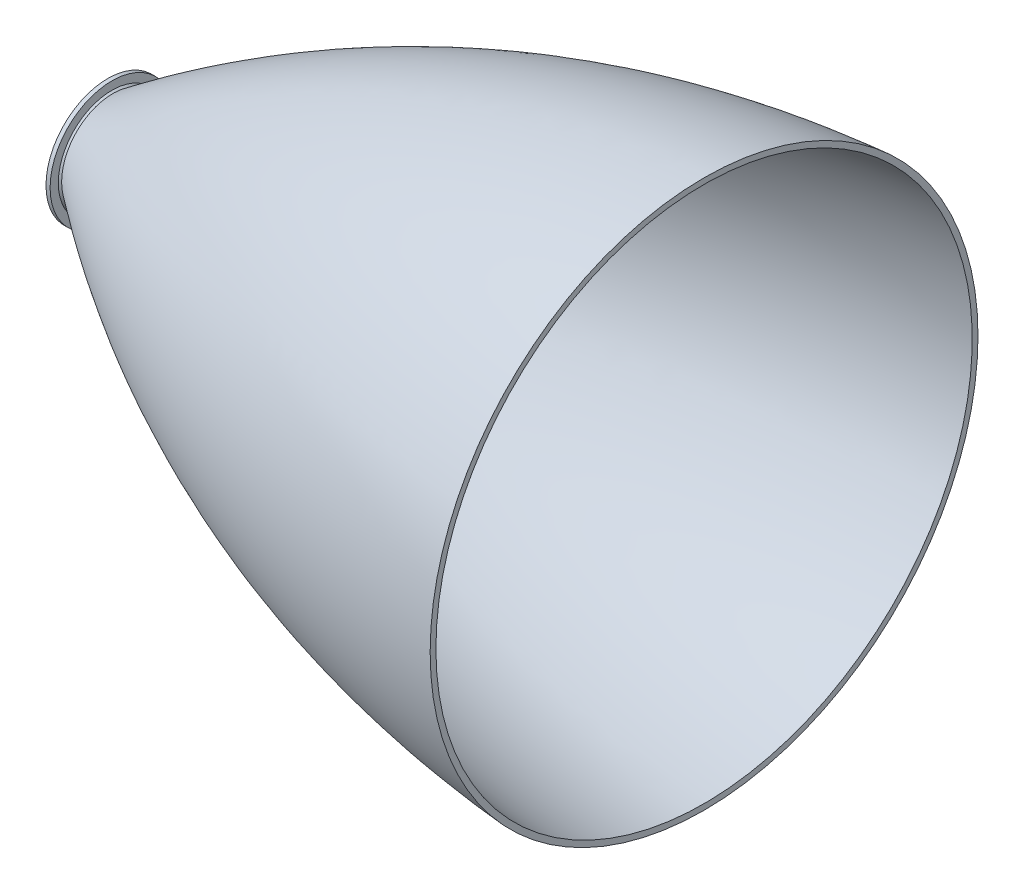
SolidWorks part; units mm, degrees
material "A286 Iron Base Superalloy"
ref_plane "Front Plane" through (0, 0, 0) normal (0, 0, 1) x (1, 0, 0)
ref_plane "Top Plane" through (0, 0, 0) normal (0, 1, 0) x (1, 0, 0)
ref_plane "Right Plane" through (0, 0, 0) normal (1, 0, 0) x (0, 0, -1)
sketch "Sketch1" plane through (0, 0, 0) normal (0, 0, 1) x (1, 0, 0)
  line L0 (-1229.8282, 0) -> (1426.3964, 0) construction
  line L1 (0, -70.104) -> (0, 70.104) construction
  line L2 (0, 0) -> (914.4, 0) construction
  line L3 (914.4, -414.655) -> (914.4, 414.655) construction
  line L5 (914.4, 423.545) -> (914.4, 414.655)
  line L6 (0, -78.994) -> (0, -70.104)
  line L7 (914.4, -423.545) -> (914.4, -414.655)
  line L8 (-412.8242, -144.8099) -> (-412.8242, 144.8099) construction
  line L9 (-412.8242, 144.8099) -> (-412.8242, 153.6999)
  line L10 (-412.8242, -144.8099) -> (-412.8242, -153.6999)
  spline S0 degree 2 poles (0, 70.104) (420.1673, 366.6312) (914.4, 414.655) knots 0 0 0 1 1 1
  spline S1 degree 2 poles (0, -70.104) (420.1673, -366.6312) (914.4, -414.655) knots 0 0 0 1 1 1
  spline S2 degree 2 poles (0, -78.994) (408.2901, -383.6129) (914.4, -423.545) knots 0 0 0 1 1 1
  spline S3 degree 2 poles (0, -70.104) (420.1673, -366.6312) (914.4, -414.655) knots 0 0 0 1 1 1
  spline S4 degree 2 poles (0, 78.994) (408.2901, 383.6129) (914.4, 423.545) knots 0 0 0 1 1 1
  spline S5 degree 2 poles (0, 70.104) (-195.4497, 157.4108) (-412.8242, 144.8099) knots 0 0 0 1 1 1
  spline S6 degree 2 poles (0, -70.104) (-195.4497, -157.4108) (-412.8242, -144.8099) knots 0 0 0 1 1 1
  spline S7 degree 2 poles (0, -78.994) (-192.7304, -176.7061) (-412.8242, -153.6999) knots 0 0 0 1 1 1
  spline S9 degree 2 poles (0, 78.994) (-192.7304, 176.7061) (-412.8242, 153.6999) knots 0 0 0 1 1 1
  point P8 (0, 0)
  point P14 (914.4, 0)
  point P22 (-412.8242, 0)
  point P23 (500.3201, 414.3107)
  point P27 (653.7474, 453.3644)
  point P29 (443.9438, 375.9514)
  point P30 (393.8482, 306.7474)
  point P31 (0, 0)
  point P32 (452.9073, 324.8925)
  dimension "D4" = 8.89
  dimension "D1" = 140.208
  dimension "D2" = 914.4
  dimension "D3" = 829.31
  dimension "D5" = 8.89
  dimension "D6" = 8.89
  dimension "D7" = 289.6197
revolve "Revolve3" add sketch "Sketch1" angle 360 about L0
ref_plane "Plane1" through (0, 0, 0) normal (1, 0, 0) x (0, 0, -1)
ref_plane "Plane2" through (-7.62, 0, 0) normal (-1, 0, 0) x (0, 0, 1)
sketch "Sketch4" plane through (-7.62, 0, 0) normal (-1, 0, 0) x (0, 0, 1)
  line L1 (-1213.2286, 638.9142) -> (1085.9115, 638.9142)
  line L2 (-1213.2286, 638.9142) -> (-1213.2286, -445.9528)
  line L3 (-1213.2286, -445.9528) -> (1085.9115, -445.9528)
  line L4 (1085.9115, 638.9142) -> (1085.9115, -445.9528)
extrude "Cut-Extrude1" cut sketch "Sketch4" along normal blind 554.228
sketch "Sketch5" plane through (-7.62, 0, 0) normal (-1, 0, 0) x (0, 0, 1)
  circle A0 centre (0, 0) radius 95.5048
  circle A1 centre (0, 0) radius 82.8048 construction
  circle A2 centre (0, 0) radius 82.8048
  dimension "D1" = 12.7
extrude "Boss-Extrude1" add sketch "Sketch5" against normal blind 6.35 separate body
